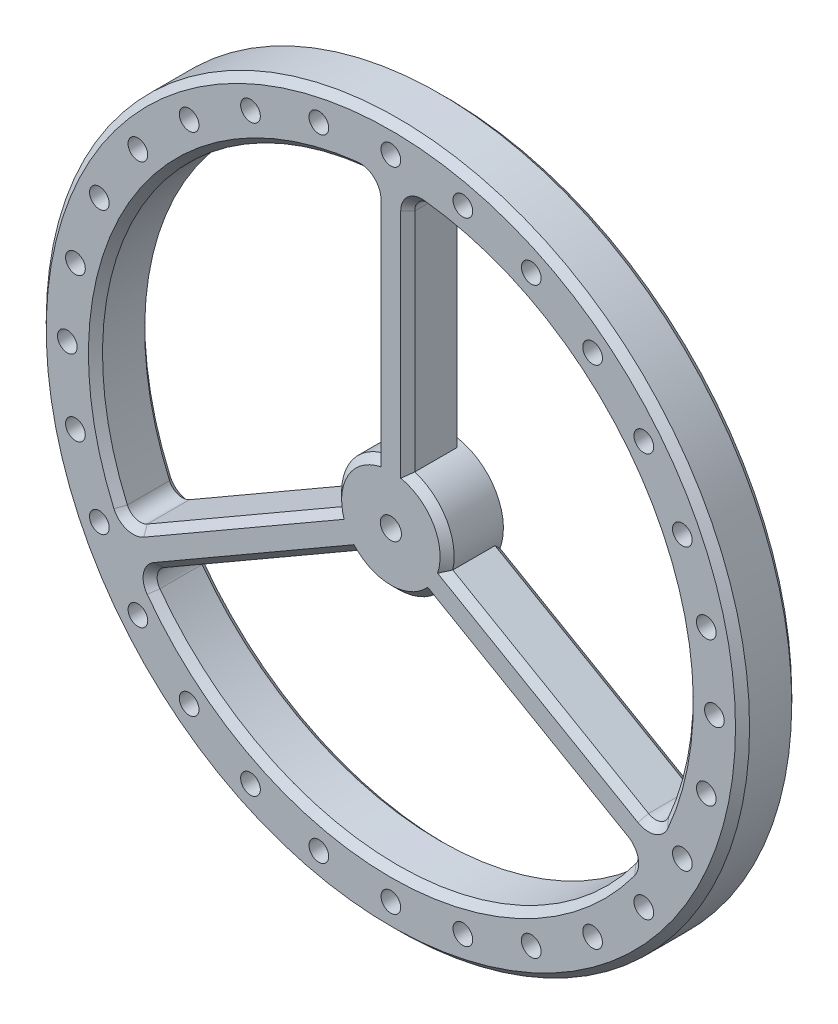
SolidWorks part; units mm, degrees
ref_plane "Front Plane" through (0, 0, 0) normal (0, 0, 1) x (1, 0, 0)
ref_plane "Top Plane" through (0, 0, 0) normal (0, 1, 0) x (1, 0, 0)
ref_plane "Right Plane" through (0, 0, 0) normal (1, 0, 0) x (0, 0, -1)
sketch "Sketch1" plane through (0, 0, 0) normal (0, 0, 1) x (1, 0, 0)
  circle A0 centre (0, 0) radius 62.5
  circle A2 centre (0, 0) radius 52.5
  circle A3 centre (0, 0) radius 57.5 construction
  dimension "D1" = 125
  dimension "D2" = 10
  dimension "D3" = 5
extrude "Boss-Extrude1" add sketch "Sketch1" against normal blind 10
sketch "Sketch2" plane through (0, 0, 0) normal (0, 0, 1) x (1, 0, 0)
  line L0 (1.0981, -4.0981) -> (43.892, -28.8052)
  line L5 (4.0981, 1.0981) -> (46.892, -23.609)
  line L6 (-4.0981, 1.0981) -> (-46.892, -23.609)
  line L11 (-1.0981, -4.0981) -> (-43.892, -28.8052)
  line L14 (-3, 3) -> (-3, 52.4142)
  line L15 (3, 3) -> (3, 52.4142)
  circle A0 centre (0, 0) radius 52.5 construction
  circle A2 centre (0, 0) radius 10
  arc A3 (3, 52.4142) -> (-3, 52.4142) centre (0, 0) ccw
  arc A5 (43.892, -28.8052) -> (46.892, -23.609) centre (0, 0) ccw
  arc A6 (3, 52.4142) -> (-3, 52.4142) centre (0, 0) ccw
  arc A8 (-46.892, -23.609) -> (-43.892, -28.8052) centre (0, 0) ccw
  point P0 (0, 0)
  point P6 (0, 0)
  point P20 (0, 0)
  dimension "D3" = 20
  dimension "D1" = 3
extrude "Boss-Extrude5" add sketch "Sketch2" against normal blind 10
sketch "Sketch3" plane through (0, 0, -10) normal (0, 0, 1) x (1, 0, 0)
  line L1 (0, 6) -> (-5.1962, 3)
  line L2 (-5.1962, 3) -> (-5.1962, -3)
  line L3 (-5.1962, -3) -> (0, -6)
  line L4 (0, -6) -> (5.1962, -3)
  line L5 (5.1962, -3) -> (5.1962, 3)
  line L6 (5.1962, 3) -> (0, 6)
  circle A0 centre (0, 0) radius 5.1962 construction
  dimension "D1" = 12
extrude "Cut-Extrude2" cut sketch "Sketch3" along normal blind 7.25
sketch "Sketch4" plane through (0, 0, 0) normal (0, 0, 1) x (1, 0, 0)
  circle A0 centre (0, 0) radius 1.875
  dimension "D1" = 3.75
extrude "Cut-Extrude3" cut sketch "Sketch4" against normal blind 6
sketch "Sketch5" plane through (0, 0, 0) normal (0, 0, 1) x (1, 0, 0)
  circle A0 centre (0, 0) radius 62.5 construction
  circle A1 centre (0, 0) radius 62.5 construction
  circle A2 centre (12.795, 56.0584) radius 1.75
  circle A3 centre (0, 57.5) radius 1.75
  circle A4 centre (0, 0) radius 57.5
  circle A5 centre (0, 0) radius 57.5 construction
  circle A6 centre (24.9483, 51.8057) radius 1.75
  circle A7 centre (35.8507, 44.9553) radius 1.75
  circle A8 centre (44.9553, 35.8507) radius 1.75
  circle A9 centre (51.8057, 24.9483) radius 1.75
  circle A10 centre (56.0584, 12.795) radius 1.75
  circle A11 centre (57.5, 0) radius 1.75
  circle A12 centre (56.0584, -12.795) radius 1.75
  circle A13 centre (51.8057, -24.9483) radius 1.75
  circle A14 centre (44.9553, -35.8507) radius 1.75
  circle A15 centre (35.8507, -44.9553) radius 1.75
  circle A16 centre (24.9483, -51.8057) radius 1.75
  circle A17 centre (12.795, -56.0584) radius 1.75
  circle A18 centre (0, -57.5) radius 1.75
  circle A19 centre (-12.795, -56.0584) radius 1.75
  circle A20 centre (-24.9483, -51.8057) radius 1.75
  circle A21 centre (-35.8507, -44.9553) radius 1.75
  circle A22 centre (-44.9553, -35.8507) radius 1.75
  circle A23 centre (-51.8057, -24.9483) radius 1.75
  circle A24 centre (-56.0584, -12.795) radius 1.75
  circle A25 centre (-57.5, 0) radius 1.75
  circle A26 centre (-56.0584, 12.795) radius 1.75
  circle A27 centre (-51.8057, 24.9483) radius 1.75
  circle A28 centre (-44.9553, 35.8507) radius 1.75
  circle A29 centre (-35.8507, 44.9553) radius 1.75
  circle A30 centre (-24.9483, 51.8057) radius 1.75
  circle A31 centre (-12.795, 56.0584) radius 1.75
  point P5 (0, 0)
  point P65 (0, 0)
  dimension "D2" = 3.5
  dimension "D1" = 5
  dimension "D3" = 28
extrude "Cut-Extrude4" cut sketch "Sketch5" against normal blind 5
fillet "Fillet1" radius 2.5 6 edges at (3, 52.4142, -5) (-3, 52.4142, -5) (46.892, -23.609, -5) (43.892, -28.8052, -5) (-43.892, -28.8052, -5) (-46.892, -23.609, -5)
chamfer "Chamfer1" distance 1.25 angle 45 35 edges at (62.5, 0, -10) (62.5, 0, 0) (8.6603, 5, 0) (3, 29.618, -10) (3, 29.618, 0) (-3, 29.618, 0) (-3, 29.618, -10) (-8.6603, 5, 0) (45.4663, 26.25, -10) (45.4663, 26.25, 0) (3.8323, 51.559, -10) (3.8323, 51.559, 0) (-45.4663, 26.25, 0) (-45.4663, 26.25, -10) (-3.8323, 51.559, -10) (-3.8323, 51.559, 0) (27.1499, -12.2109, 0) (27.1499, -12.2109, -10) (46.5676, -22.4607, -10) (46.5676, -22.4607, 0) (-27.1499, -12.2109, -10) (-27.1499, -12.2109, 0) (-46.5676, -22.4607, -10) (-46.5676, -22.4607, 0) (42.7353, -29.0984, -10) (42.7353, -29.0984, 0) (24.1499, -17.4071, -10) (24.1499, -17.4071, 0) (0, -10, 0) (-24.1499, -17.4071, 0) (-24.1499, -17.4071, -10) (-42.7353, -29.0984, -10) (-42.7353, -29.0984, 0) (0, -52.5, 0) (0, -52.5, -10)
